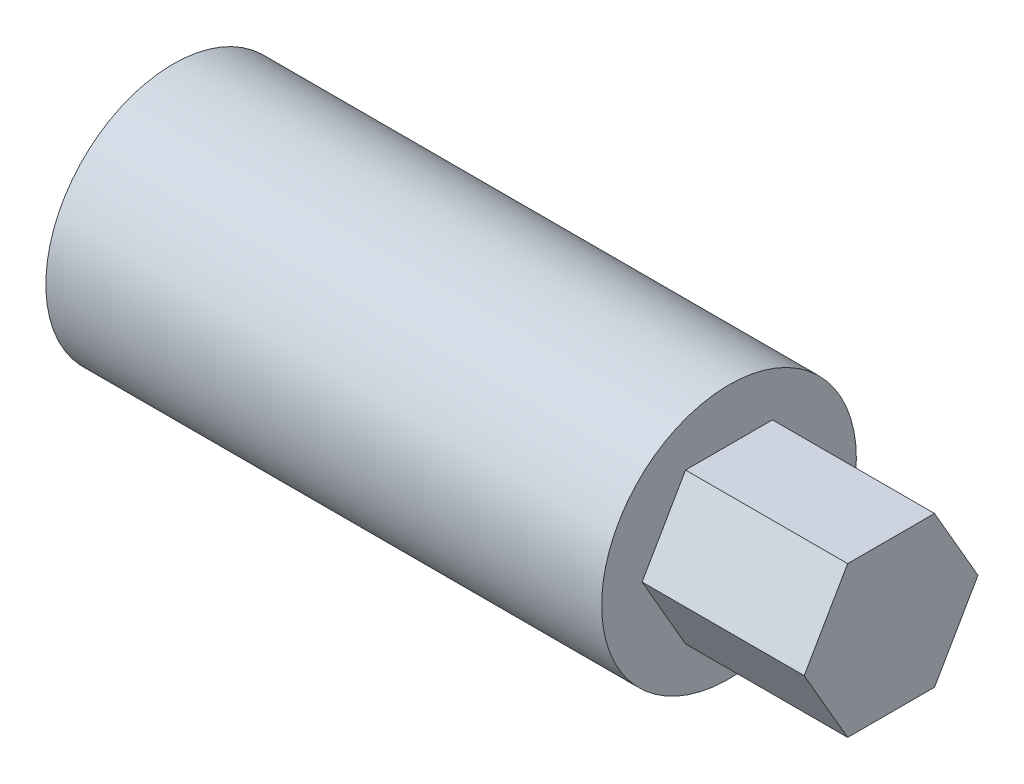
SolidWorks part; units mm, degrees
ref_plane "Plano frontal" through (0, 0, 0) normal (1, 0, 0) x (0, 1, 0)
ref_plane "Plano superior" through (0, 0, 0) normal (0, 0, 1) x (0, 1, 0)
ref_plane "Plano direito" through (0, 0, 0) normal (0, 1, 0) x (-1, 0, 0)
sketch "Esboço1" plane through (0, 0, 0) normal (1, 0, 0) x (0, 1, 0)
  circle A0 centre (0, 0) radius 11
  dimension "D1" = 22
extrude "Ressalto-extrusão1" add sketch "Esboço1" along normal blind 62
sketch "Esboço2" plane through (62, 0, 0) normal (1, 0, 0) x (0, 1, 0)
  line L1 (0, 7.5056) -> (-6.5, 3.7528)
  line L2 (-6.5, 3.7528) -> (-6.5, -3.7528)
  line L3 (-6.5, -3.7528) -> (0, -7.5056)
  line L4 (0, -7.5056) -> (6.5, -3.7528)
  line L5 (6.5, -3.7528) -> (6.5, 3.7528)
  line L6 (6.5, 3.7528) -> (0, 7.5056)
  circle A0 centre (0, 0) radius 6.5 construction
  circle A1 centre (0, 0) radius 11
  circle A2 centre (0, 0) radius 11 construction
  dimension "D1" = 13
extrude "Corte-extrusão1" cut sketch "Esboço2" against normal blind 14 contours A1
